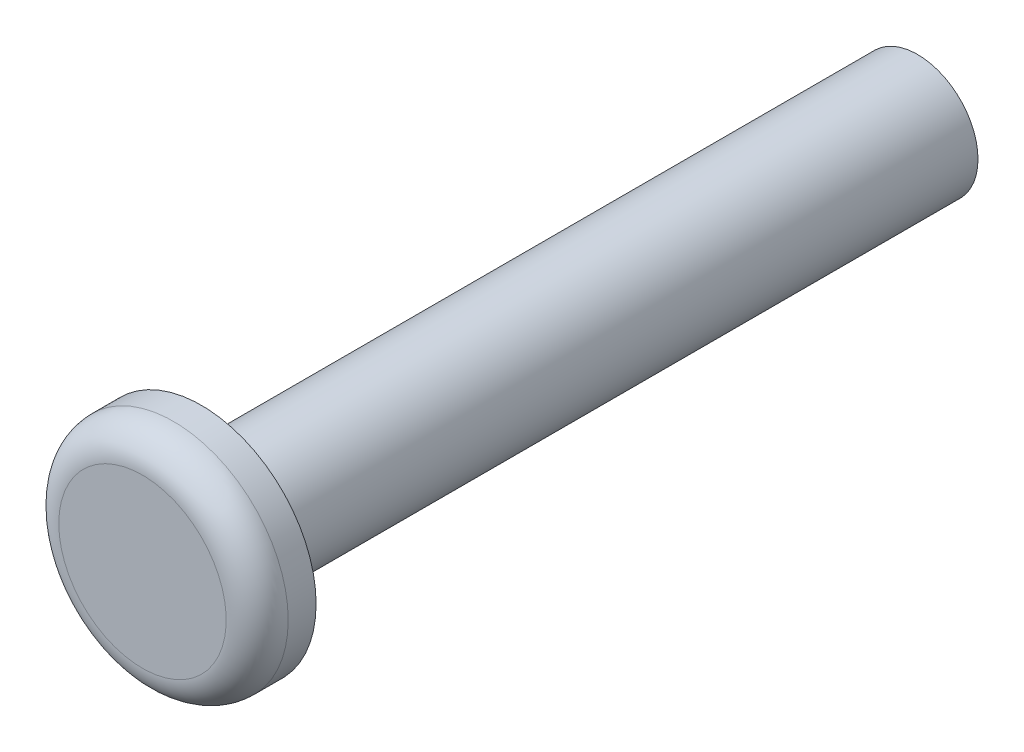
SolidWorks part; units mm, degrees
material "Niedriglegierter Stahlguss"
ref_plane "Front Plane" through (0, 0, 0) normal (0, 0, 1) x (1, 0, 0)
ref_plane "Top Plane" through (0, 0, 0) normal (0, 1, 0) x (1, 0, 0)
ref_plane "Right Plane" through (0, 0, 0) normal (1, 0, 0) x (0, 0, -1)
sketch "Sketch1" plane through (0, 0, 0) normal (1, 0, 0) x (0, 0, -1)
  line L0 (1.9, 1.95) -> (1.9, 3.7)
  line L1 (0, 0) -> (25, 0)
  line L3 (1.9, 1.95) -> (25, 1.95)
  line L4 (25, 0) -> (25, 1.95)
  line L5 (1.9, 3.7) -> (0, 3.7)
  line L6 (0, 3.7) -> (0, 0)
  dimension "D1" = 25
  dimension "D2" = 1.95
  dimension "D3" = 3.7
  dimension "D4" = 1.9
revolve "Revolve1" add sketch "Sketch1" angle 360 about L1
fillet "Fillet1" radius 1 1 edges at (3.7, 0, 0)
